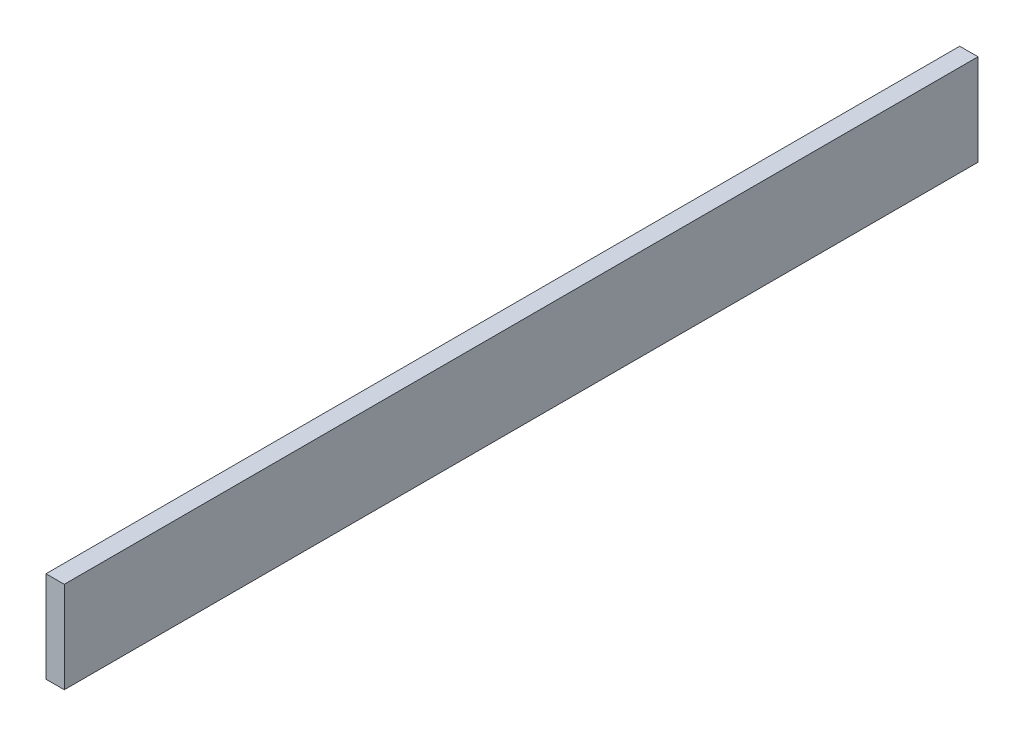
SolidWorks part; units mm, degrees
ref_plane "Plan de face" through (0, 0, 0) normal (0, 0, 1) x (1, 0, 0)
ref_plane "Plan de dessus" through (0, 0, 0) normal (0, 1, 0) x (1, 0, 0)
ref_plane "Plan de droite" through (0, 0, 0) normal (1, 0, 0) x (0, 0, -1)
sketch "Esquisse2" plane through (0, 0, 0) normal (0, 0, 1) x (1, 0, 0)
  line L1 (-10, -50) -> (10, -50)
  line L2 (-10, -50) -> (-10, 50)
  line L3 (-10, 50) -> (10, 50)
  line L4 (10, -50) -> (10, 50)
  line L5 (-10, -50) -> (10, 50) construction
  line L6 (-10, 50) -> (10, -50) construction
  point P0 (0, 0)
  dimension "D1" = 20
  dimension "D2" = 100
extrude "Boss.-Extru.1" add sketch "Esquisse2" along normal blind 1000 contours L3 L4 L1 L2
